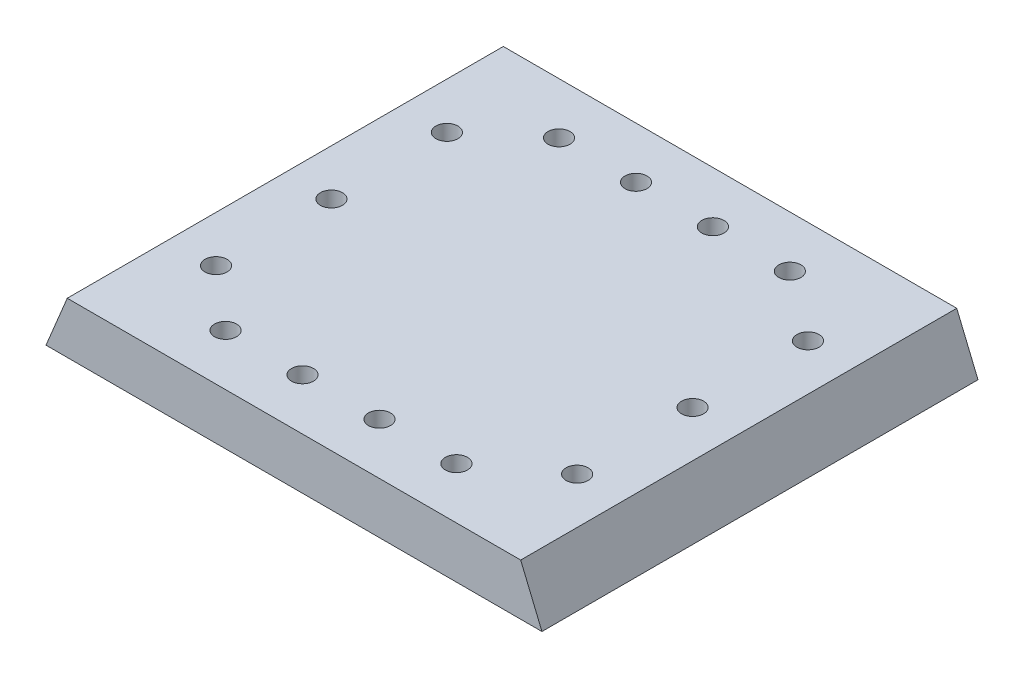
SolidWorks part; units mm, degrees
ref_plane "Front Plane" through (0, 0, 0) normal (0, 0, 1) x (1, 0, 0)
ref_plane "Top Plane" through (0, 0, 0) normal (0, 1, 0) x (1, 0, 0)
ref_plane "Right Plane" through (0, 0, 0) normal (1, 0, 0) x (0, 0, -1)
sketch "Sketch2" plane through (0, 0, 0) normal (0, 0, 1) x (1, 0, 0)
  line L0 (0, 0) -> (96.6743, 0)
  line L1 (96.6743, 0) -> (92.5321, 10)
  line L2 (92.5321, 10) -> (4.1421, 10)
  line L3 (4.1421, 10) -> (0, 0)
  dimension "D1" = 88.39
  dimension "D2" = 112.5
  dimension "D3" = 112.5
  dimension "D4" = 10
extrude "Boss-Extrude1" add sketch "Sketch2" along normal blind 85
sketch "Sketch3" plane through (0, 0, 0) normal (0, -1, 0) x (1, 0, 0)
  line L0 (0, 85) -> (0, 0) construction
  line L1 (0, 85) -> (96.6743, 85) construction
  line L2 (0, 42.5) -> (96.6743, 42.5) construction
  line L3 (96.6743, 85) -> (96.6743, 0) construction
  circle A0 centre (25, 75) radius 2.15
  circle A1 centre (25, 10) radius 2.15
  dimension "D1" = 4.3
  dimension "D2" = 25
  dimension "D3" = 10
extrude "Cut-Extrude1" cut sketch "Sketch3" against normal blind 85
pattern_linear "LPattern1" count 4 spacing 15 along (1, 0, 0) of "Cut-Extrude1"
sketch "Sketch4" plane through (0, 10, 0) normal (0, 1, 0) x (1, 0, 0)
  line L0 (92.5321, -85) -> (4.1421, -85) construction
  line L1 (92.5321, 0) -> (4.1421, 0) construction
  line L2 (92.5321, -85) -> (92.5321, 0) construction
  line L3 (48.3371, 0) -> (48.3371, -85) construction
  circle A0 centre (83.5321, -20) radius 2.15
  circle A1 centre (83.5321, -42.5) radius 2.15
  circle A2 centre (83.5321, -65) radius 2.15
  circle A3 centre (13.1421, -65) radius 2.15
  circle A4 centre (13.1421, -42.5) radius 2.15
  circle A5 centre (13.1421, -20) radius 2.15
  dimension "D1" = 4.3
  dimension "D2" = 4.3
  dimension "D3" = 4.3
  dimension "D4" = 20
  dimension "D5" = 20
  dimension "D6" = 42.5
  dimension "D7" = 9
extrude "Cut-Extrude2" cut sketch "Sketch4" against normal blind 85
